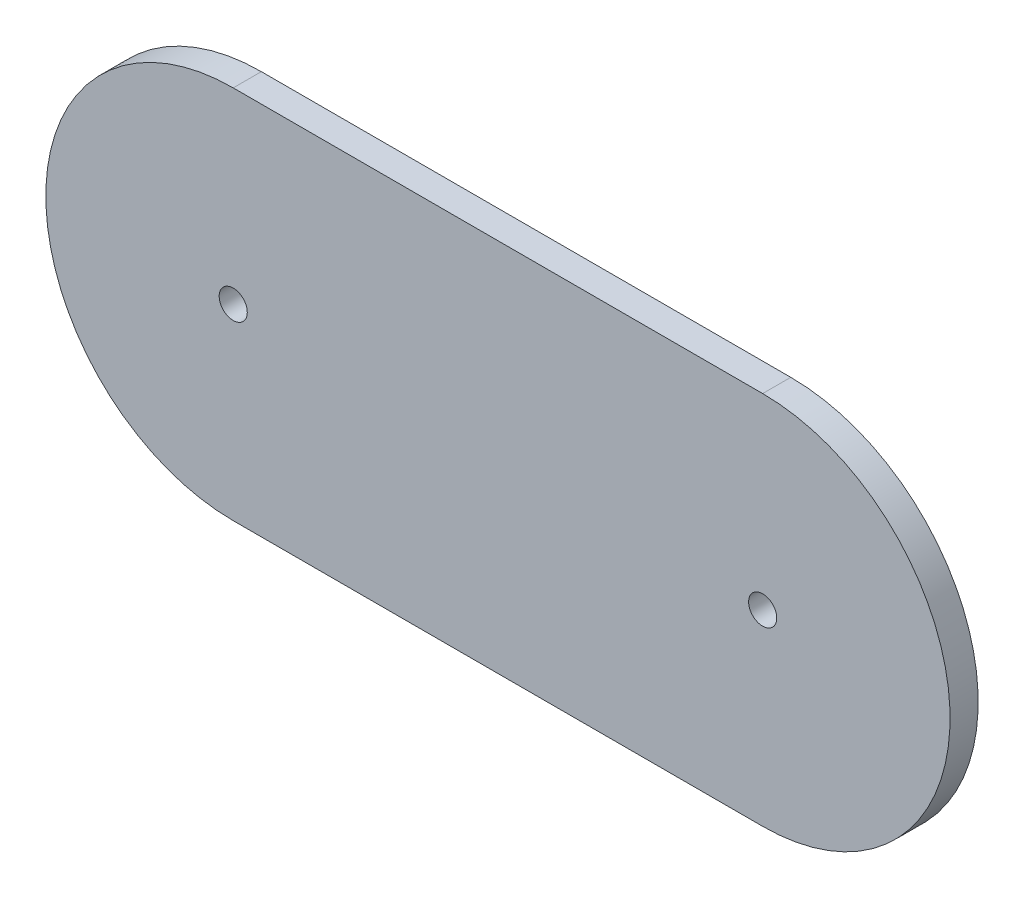
SolidWorks part; units mm, degrees
ref_plane "Front Plane" through (0, 0, 0) normal (0, 0, 1) x (1, 0, 0)
ref_plane "Top Plane" through (0, 0, 0) normal (0, 1, 0) x (1, 0, 0)
ref_plane "Right Plane" through (0, 0, 0) normal (1, 0, 0) x (0, 0, -1)
sketch "Sketch1" plane through (0, 0, 0) normal (0, 0, 1) x (1, 0, 0)
  line L0 (-28.25, 20) -> (-28.25, -20) construction
  line L1 (-28.25, 20) -> (28.25, 20)
  line L2 (28.25, 20) -> (28.25, -20) construction
  line L3 (-28.25, -20) -> (28.25, -20)
  line L5 (-28.25, 20) -> (28.25, -20) construction
  line L6 (-28.25, -20) -> (28.25, 20) construction
  arc A0 (-28.25, 20) -> (-28.25, -20) centre (-28.25, 0) ccw
  arc A1 (28.25, -20) -> (28.25, 20) centre (28.25, 0) ccw
  circle A2 centre (-28.25, 0) radius 1.5
  circle A3 centre (28.25, 0) radius 1.5
  point P0 (0, 0)
  dimension "D3" = 3
  dimension "D4" = 3
  dimension "D1" = 56.5
  dimension "D2" = 40
extrude "Boss-Extrude1" add sketch "Sketch1" along normal blind 3
